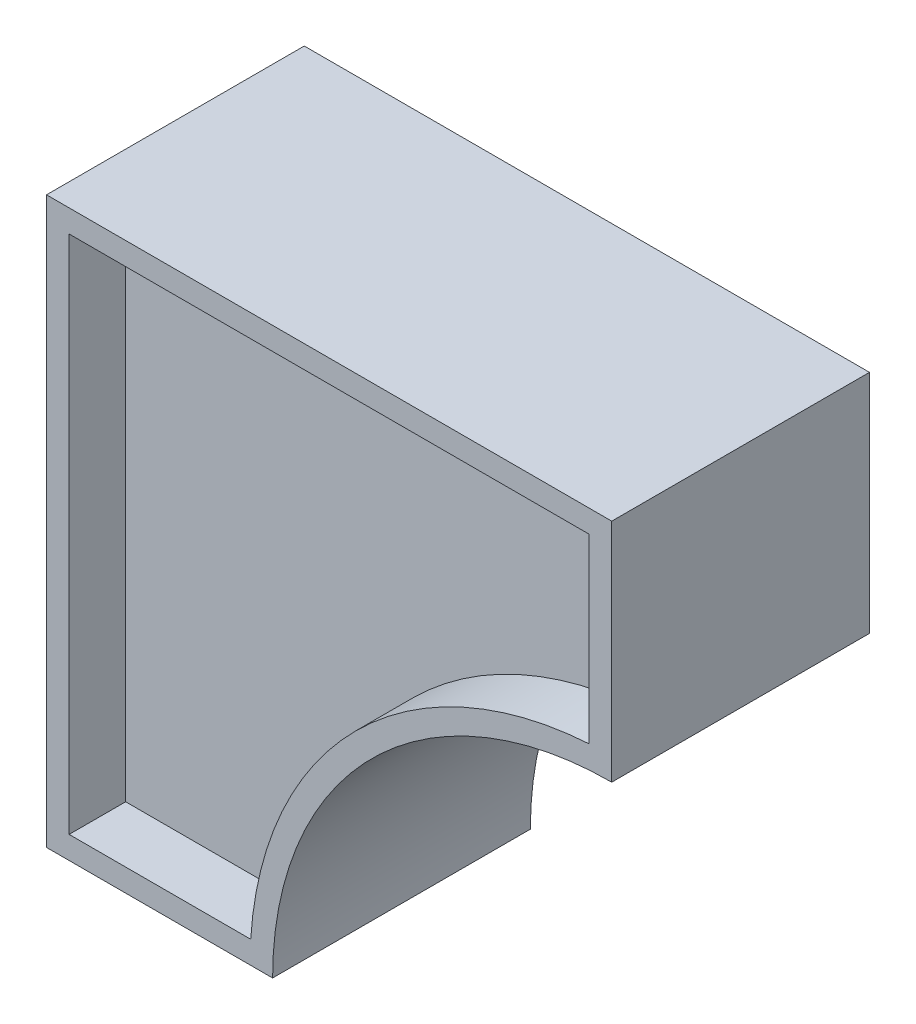
SolidWorks part; units mm, degrees
ref_plane "Front Plane" through (0, 0, 0) normal (0, 0, 1) x (1, 0, 0)
ref_plane "Top Plane" through (0, 0, 0) normal (0, 1, 0) x (1, 0, 0)
ref_plane "Right Plane" through (0, 0, 0) normal (1, 0, 0) x (0, 0, -1)
sketch "Sketch1" plane through (0, 0, 0) normal (0, 0, 1) x (1, 0, 0)
  line L0 (0, 0) -> (63.5, 0)
  line L1 (63.5, 0) -> (63.5, -25.4)
  line L2 (0, 0) -> (0, -63.5)
  line L3 (0, -63.5) -> (25.4, -63.5)
  line L4 (63.5, -63.5) -> (63.5, -25.4) construction
  line L5 (25.4, -63.5) -> (63.5, -63.5) construction
  arc A0 (63.5, -25.4) -> (25.4, -63.5) centre (63.5, -63.5) ccw
  point P3 (76.9137, -29.5054)
  dimension "D1" = 38.1
  dimension "D2" = 25.4
extrude "Boss-Extrude2" add sketch "Sketch1" along normal blind 28.956
sketch "Sketch2" plane through (0, 0, 28.956) normal (0, 0, 1) x (1, 0, 0)
  line L8 (2.54, -2.54) -> (2.54, -60.96)
  line L9 (2.54, -60.96) -> (22.9395, -60.96)
  line L10 (60.96, -22.9395) -> (60.96, -2.54)
  line L11 (60.96, -2.54) -> (2.54, -2.54)
  line L12 (2.54, -2.54) -> (2.54, -60.96)
  line L13 (2.54, -60.96) -> (22.9395, -60.96)
  line L14 (60.96, -22.9395) -> (60.96, -2.54)
  line L15 (60.96, -2.54) -> (2.54, -2.54)
  arc A2 (60.96, -22.9395) -> (22.9395, -60.96) centre (63.5, -63.5) ccw
  arc A3 (60.96, -22.9395) -> (22.9395, -60.96) centre (63.5, -63.5) ccw
  dimension "D1" = 2.54
extrude "Cut-Extrude1" cut sketch "Sketch2" against normal blind 6.35
sketch "Sketch3" plane through (0, 0, 0) normal (-1, 0, 0) x (0, 0, 1)
  line L0 (15.1056, -8.1692) -> (15.1056, -43.8542) construction
  line L1 (20.1856, -8.1692) -> (20.1856, -43.8542)
  line L2 (10.0256, -8.1692) -> (10.0256, -43.8542)
  line L3 (20.1856, -8.1692) -> (10.0256, -8.1692)
  line L4 (20.1856, -43.8542) -> (10.0256, -43.8542)
  point P6 (11.0709, -8.1692)
  dimension "D1" = 5.08
  dimension "D2" = 5.08
